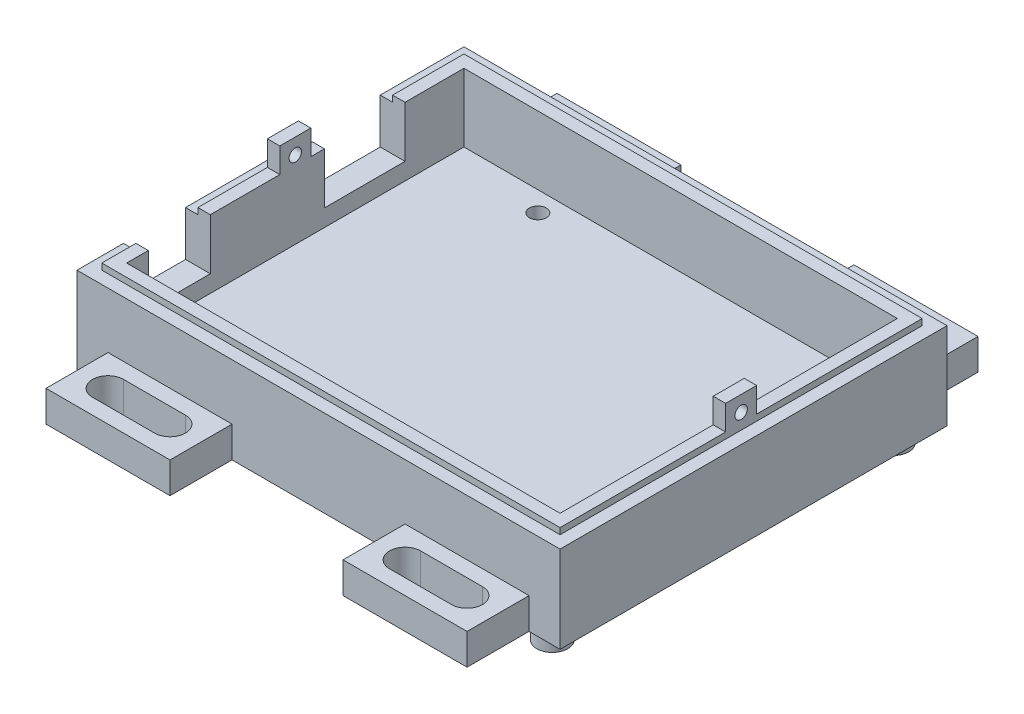
SolidWorks part; units mm, degrees
material "ABS"
ref_plane "Front Plane" through (0, 0, 0) normal (0, 0, 1) x (1, 0, 0)
ref_plane "Top Plane" through (0, 0, 0) normal (0, 1, 0) x (1, 0, 0)
ref_plane "Right Plane" through (0, 0, 0) normal (1, 0, 0) x (0, 0, -1)
sketch "Sketch1" plane through (0, 0, 0) normal (0, 1, 0) x (1, 0, 0)
  line L0 (-4, -4) -> (-4, 58.4)
  line L1 (0, 0) -> (69.9, 0)
  line L2 (0, 0) -> (0, 54.4)
  line L3 (0, 54.4) -> (69.9, 54.4)
  line L4 (69.9, 0) -> (69.9, 54.4)
  line L5 (-4, 58.4) -> (73.9, 58.4)
  line L6 (73.9, -4) -> (73.9, 58.4)
  line L7 (-4, -4) -> (73.9, -4)
  dimension "D1" = 54.4
  dimension "D2" = 69.9
  dimension "D3" = 4
extrude "Boss-Extrude1" add sketch "Sketch1" along normal blind 10
sketch "Sketch2" plane through (0, 0, 0) normal (0, 1, 0) x (1, 0, 0)
  line L0 (-4, 58.4) -> (-4, -4) construction
  line L1 (-4, 58.4) -> (-4, -4)
  line L2 (73.9, 58.4) -> (-4, 58.4) construction
  line L3 (-4, -4) -> (73.9, -4) construction
  line L4 (73.9, -4) -> (73.9, 58.4) construction
  line L5 (73.9, 58.4) -> (-4, 58.4)
  line L6 (-4, -4) -> (73.9, -4)
  line L7 (73.9, -4) -> (73.9, 58.4)
extrude "Boss-Extrude2" add sketch "Sketch2" against normal blind 4
sketch "Sketch7" plane through (0, 10, 0) normal (0, 1, 0) x (1, 0, 0)
  line L0 (73.9, -4) -> (73.9, 58.4) construction
  line L1 (71.9, -2) -> (-2, -2)
  line L2 (71.9, -2) -> (71.9, 56.4)
  line L3 (71.9, 56.4) -> (-2, 56.4)
  line L4 (-2, -2) -> (-2, 56.4)
  line L5 (73.9, 58.4) -> (-4, 58.4) construction
  line L6 (-4, -4) -> (73.9, -4) construction
  line L7 (-4, 58.4) -> (-4, -4) construction
  line L9 (69.9, 0) -> (0, 0)
  line L10 (69.9, 0) -> (69.9, 54.4)
  line L11 (69.9, 54.4) -> (0, 54.4)
  line L12 (0, 0) -> (0, 54.4)
  dimension "D1" = 2
  dimension "D2" = 2
  dimension "D3" = 2
  dimension "D4" = 2
extrude "Boss-Extrude4" add sketch "Sketch7" along normal blind 1
sketch "Sketch3" plane through (-4, 0, 0) normal (-1, 0, 0) x (0, 0, 1)
  line L0 (-58.4, 10) -> (-58.4, -4) construction
  line L2 (-58.4, -4) -> (4, -4) construction
  line L3 (-44.9, 2.75) -> (-44.9, 10)
  line L4 (-58.4, 10) -> (4, 10) construction
  line L5 (-44.9, 2.75) -> (-31.9, 2.75)
  line L6 (-31.9, 2.75) -> (-31.9, 10)
  line L7 (-31.9, 10) -> (-44.9, 10)
  dimension "D1" = 13.5
  dimension "D2" = 6.75
  dimension "D3" = 13
extrude "Cut-Extrude1" cut sketch "Sketch3" against normal up to next
sketch "Sketch4" plane through (-4, 0, 0) normal (-1, 0, 0) x (0, 0, 1)
  line L0 (4, -4) -> (-3.5, -4)
  line L1 (-58.4, -4) -> (4, -4) construction
  line L2 (-3.5, -4) -> (-3.5, 2.75)
  line L3 (-3.5, 2.75) -> (-13.5, 2.75)
  line L4 (-13.5, 2.75) -> (-13.5, 10)
  line L5 (-31.9, 10) -> (4, 10) construction
  line L6 (-13.5, 10) -> (-3.5, 10)
  line L7 (-3.5, 10) -> (-3.5, 2.75)
  line M8 (4, 10) -> (-31.9, 10)
  dimension "D1" = 7.5
  dimension "D2" = 6.75
  dimension "D3" = 10
extrude "Cut-Extrude2" cut sketch "Sketch4" against normal up to next contours L7 L4 L3 M8
sketch "Sketch5" plane through (0, -4, 0) normal (0, -1, 0) x (-1, 0, 0)
  circle A1 centre (-65.9447, 7.9913) radius 1.3693
  circle A4 centre (-15.1574, 51.1585) radius 1.3692
  circle A5 centre (-65.9447, 35.9185) radius 1.3693
  circle A6 centre (-14.0144, 3.2414) radius 1.3692
extrude "Cut-Extrude4" cut sketch "Sketch5" against normal mid plane 50
sketch "Sketch6" plane through (0, -4, 0) normal (0, -1, 0) x (-1, 0, 0)
  line L0 (-0.95, -0.3) -> (-68.95, -0.3) construction
  line L1 (-68.95, -0.3) -> (-68.95, 54.7) construction
  line L2 (-68.95, 54.7) -> (-0.95, 54.7) construction
  line L3 (-0.95, 54.7) -> (-0.95, -0.3) construction
  line L4 (-73.9, 27.2) -> (45.8322, 27.2) construction
  line L5 (-73.9, -4) -> (-73.9, 58.4) construction
  line L6 (-34.95, -4) -> (-34.95, 71.4266) construction
  line L7 (4, -4) -> (-73.9, -4) construction
  line L8 (-34.95, -0.3) -> (-34.95, 67.6095) construction
  line L9 (-68.95, 27.2) -> (55.6842, 27.2) construction
  circle A0 centre (-0.95, -0.3) radius 2.5
  circle A1 centre (-0.95, 54.7) radius 2.5
  circle A2 centre (-68.95, 54.7) radius 2.5
  circle A3 centre (-68.95, -0.3) radius 2.5
  dimension "D1" = 5
  dimension "D2" = 68
  dimension "D3" = 55
extrude "Boss-Extrude3" add sketch "Sketch6" along normal blind 3
sketch "Sketch9" plane through (-2, 0, 0) normal (-1, 0, 0) x (0, 0, 1)
  line L0 (-56.4, 11) -> (2, 11) construction
  line L1 (-3.5, 10) -> (-13.5, 10)
  line L2 (-3.5, 10) -> (-3.5, 11)
  line L3 (-3.5, 11) -> (-13.5, 11)
  line L4 (-13.5, 10) -> (-13.5, 11)
  line L5 (-13.5, 10) -> (-3.5, 10) construction
  line L6 (-31.9, 10) -> (-44.9, 10)
  line L7 (-31.9, 10) -> (-31.9, 11)
  line L8 (-31.9, 11) -> (-44.9, 11)
  line L9 (-44.9, 10) -> (-44.9, 11)
  line L10 (-31.9, 10) -> (-13.5, 10) construction
extrude "Cut-Extrude5" cut sketch "Sketch9" against normal blind 11
sketch "Sketch11" plane through (71.9, 0, 0) normal (1, 0, 0) x (0, 0, -1)
  line L0 (27.2, 15) -> (27.2, 10) construction
  line L1 (24.7, 10) -> (29.7, 10)
  line L2 (24.7, 10) -> (24.7, 15)
  line L3 (24.7, 15) -> (29.7, 15)
  line L4 (29.7, 10) -> (29.7, 15)
  line L5 (24.7, 12.5) -> (29.7, 12.5) construction
  line L6 (27.2, 11) -> (27.2, 40.5291) construction
  line L7 (-2, 11) -> (56.4, 11) construction
  line L8 (-2, 10) -> (56.4, 10) construction
  line L9 (-2, 10) -> (56.4, 10) construction
  circle A0 centre (27.2, 12.5) radius 1
  dimension "D3" = 2
  dimension "D1" = 5
  dimension "D2" = 5
  dimension "D4" = 29.2
  dimension "D5" = 29.2
extrude "Boss-Extrude5" add sketch "Sketch11" against normal blind 2
sketch "Sketch12" plane through (-2, 0, 0) normal (-1, 0, 0) x (0, 0, 1)
  line L0 (-56.4, 10) -> (2, 10) construction
  line L1 (-27.2, 10) -> (-27.2, 16.2125) construction
  line L2 (-27.2, 15) -> (-27.2, 10) construction
  line L3 (-29.7, 10) -> (-24.7, 10)
  line L4 (-29.7, 10) -> (-29.7, 15)
  line L5 (-29.7, 15) -> (-24.7, 15)
  line L6 (-24.7, 10) -> (-24.7, 15)
  line L7 (-29.7, 12.5) -> (-24.7, 12.5) construction
  circle A0 centre (-27.2, 12.5) radius 1
  dimension "D1" = 2
  dimension "D2" = 5
  dimension "D3" = 5
extrude "Boss-Extrude6" add sketch "Sketch12" against normal blind 2
sketch "Sketch13" plane through (0, 0, -58.4) normal (0, 0, -1) x (-1, 0, 0)
  line L0 (-34.95, -4) -> (-34.95, 10) construction
  line L1 (-68.9, -4) -> (-48.9, -4)
  line L2 (-68.9, -4) -> (-68.9, 1)
  line L3 (-68.9, 1) -> (-48.9, 1)
  line L4 (-48.9, -4) -> (-48.9, 1)
  line L5 (-68.9, -1.5) -> (-48.9, -1.5) construction
  line L6 (-73.9, 10) -> (4, 10) construction
  line L7 (-73.9, -4) -> (4, -4) construction
  line L9 (-73.9, 10) -> (-73.9, -4) construction
  line L10 (-58.9, -4) -> (-58.9, 1) construction
  dimension "D1" = 5
  dimension "D2" = 20
  dimension "D3" = 5
extrude "Boss-Extrude7" add sketch "Sketch13" along normal blind 10
sketch "Sketch14" plane through (0, 1, 0) normal (0, 1, 0) x (1, 0, 0)
  line L0 (63.9, 63.4) -> (53.9, 63.4) construction
  line L1 (63.9, 60.9) -> (53.9, 60.9)
  line L2 (63.9, 65.9) -> (53.9, 65.9)
  line L3 (58.9, 68.4) -> (58.9, 58.4) construction
  line L4 (48.9, 68.4) -> (68.9, 68.4) construction
  line L5 (48.9, 58.4) -> (68.9, 58.4) construction
  line L6 (68.9, 63.4) -> (48.9, 63.4) construction
  line L7 (68.9, 68.4) -> (68.9, 58.4) construction
  line L8 (48.9, 68.4) -> (48.9, 58.4) construction
  arc A0 (63.9, 60.9) -> (63.9, 65.9) centre (63.9, 63.4) ccw
  arc A1 (53.9, 65.9) -> (53.9, 60.9) centre (53.9, 63.4) ccw
  point P2 (58.9, 63.4)
  dimension "D1" = 10
  dimension "D2" = 2.5
extrude "Cut-Extrude6" cut sketch "Sketch14" against normal blind 10
ref_plane "Plane1" through (34.95, 0, 0) normal (-1, 0, 0) x (0, 0, 1)
ref_plane "Plane2" through (0, 0, -27.2) normal (0, 0, -1) x (-1, 0, 0)
mirror "Mirror1" about plane through (0, 0, -27.2) normal (0, 0, -1) of "Cut-Extrude6", "Boss-Extrude7"
mirror "Mirror2" about plane through (34.95, 0, 0) normal (-1, 0, 0) of "Mirror1", "Boss-Extrude7", "Cut-Extrude6"
